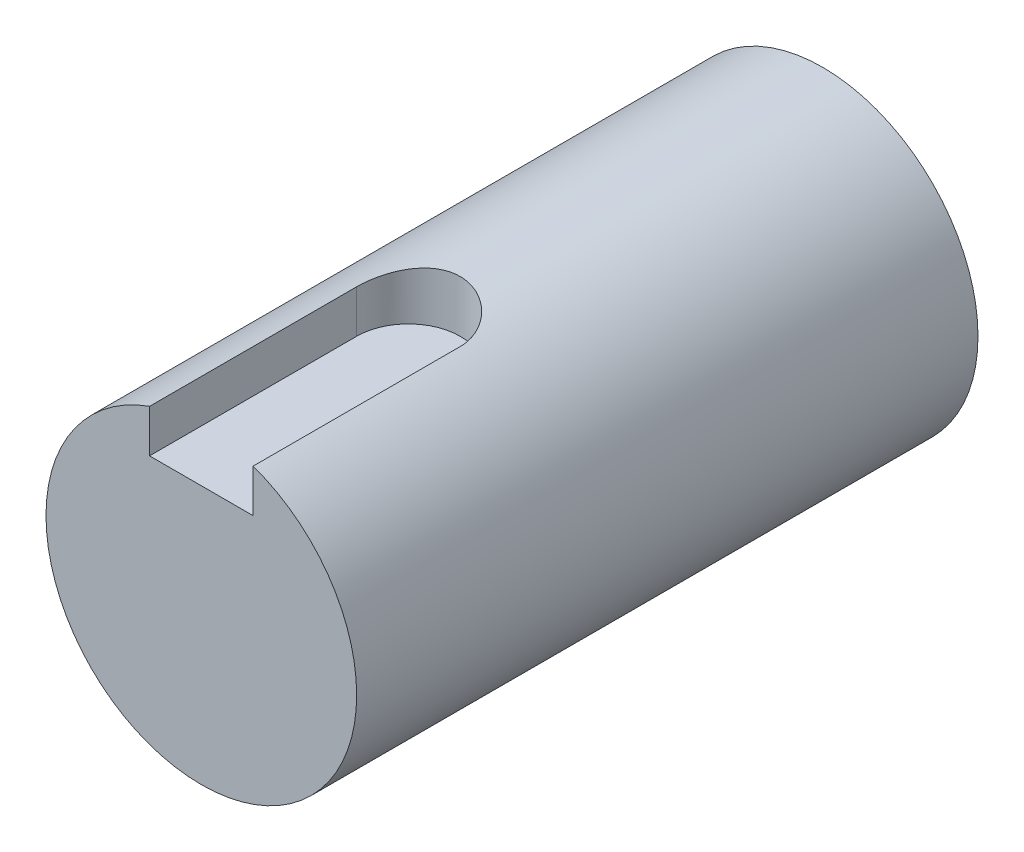
SolidWorks part; units mm, degrees
material "Alloy Steel"
ref_plane "Front Plane" through (0, 0, 0) normal (0, 0, 1) x (1, 0, 0)
ref_plane "Top Plane" through (0, 0, 0) normal (0, 1, 0) x (1, 0, 0)
ref_plane "Right Plane" through (0, 0, 0) normal (1, 0, 0) x (0, 0, -1)
sketch "Sketch2" plane through (0, 0, 0) normal (0, 0, 1) x (1, 0, 0)
  circle A0 centre (0, 0) radius 15
  dimension "D1" = 30
extrude "Boss-Extrude1" add sketch "Sketch2" along normal mid plane 60
ref_plane "Plane1" through (0, 15, 0) normal (0, 1, 0) x (1, 0, 0)
sketch "Sketch3" plane through (0, 15, 0) normal (0, 1, 0) x (1, 0, 0)
  line L0 (0, -30) -> (0, -10) construction
  line L1 (0, -16.5) -> (0, 16.5) construction
  line L2 (-5, -30) -> (-5, -10)
  line L3 (5, -30) -> (5, -10)
  line L4 (-15, -30) -> (15, -30) construction
  arc A0 (-5, -30) -> (5, -30) centre (0, -30) ccw
  arc A1 (5, -10) -> (-5, -10) centre (0, -10) ccw
  point P5 (0, -20)
  point P13 (0, -5)
  dimension "D2" = 25
  dimension "D1" = 10
extrude "Cut-Extrude1" cut sketch "Sketch3" against normal blind 5
